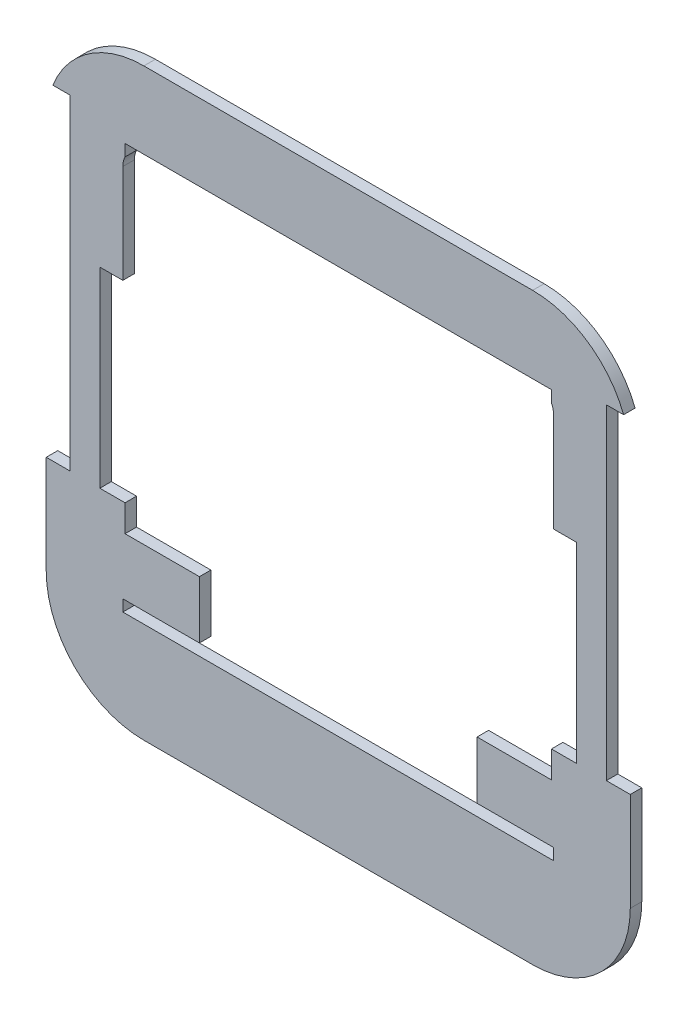
SolidWorks part; units mm, degrees
material "Teak"
ref_plane "Front Plane" through (0, 0, 0) normal (0, 0, 1) x (1, 0, 0)
ref_plane "Top Plane" through (0, 0, 0) normal (0, 1, 0) x (1, 0, 0)
ref_plane "Right Plane" through (0, 0, 0) normal (1, 0, 0) x (0, 0, -1)
sketch "Sketch1" plane through (0, 0, 0) normal (0, 0, 1) x (1, 0, 0)
  line L0 (76.25, -25) -> (70, -25)
  line L1 (70, -25) -> (70, 60)
  line L2 (70, 60) -> (74.5132, 60)
  line L6 (50.75, 76.25) -> (-50.75, 76.25)
  line L7 (-74.5132, 60) -> (-70, 60)
  line L8 (-70, 60) -> (-70, -25)
  line L9 (-70, -25) -> (-76.25, -25)
  line L10 (-76.25, -25) -> (-76.25, -50.75)
  line L11 (-50.75, -76.25) -> (50.75, -76.25)
  line L12 (76.25, -50.75) -> (76.25, -25)
  line L13 (56.25, -50) -> (56.25, -47)
  line L14 (49.7468, -50) -> (56.25, -50)
  line L15 (-49.7468, -50) -> (49.7468, -50)
  line L16 (-56.25, -50) -> (-49.7468, -50)
  line L17 (-56.25, -47) -> (-56.25, -50)
  line L18 (-49.7468, -47) -> (-56.25, -47)
  line L19 (-36.25, -47) -> (-49.7468, -47)
  line L20 (-36.25, -32) -> (-36.25, -47)
  line L21 (-55.6698, -32) -> (-36.25, -32)
  line L24 (-62.25, -25) -> (-56.25, -25)
  line L25 (-62.25, 25) -> (-62.25, -25)
  line L26 (-56.25, 25) -> (-62.25, 25)
  line L27 (-56.25, 50.75) -> (-56.25, 25)
  line L28 (-55.6698, 56.25) -> (-55.6698, 53.2088)
  line L29 (55.6698, 56.25) -> (-55.6698, 56.25)
  line L30 (55.6698, 53.2088) -> (55.6698, 56.25)
  line L31 (56.25, 25) -> (56.25, 50.75)
  line L32 (62.25, 25) -> (56.25, 25)
  line L33 (62.25, -25) -> (62.25, 25)
  line L34 (56.25, -25) -> (62.25, -25)
  line L37 (36.25, -32) -> (55.6698, -32)
  line L38 (36.25, -47) -> (36.25, -32)
  line L39 (49.7468, -47) -> (36.25, -47)
  line L40 (56.25, -47) -> (49.7468, -47)
  line L41 (55.6698, -32) -> (55.6698, -25)
  line L42 (55.6698, -25) -> (56.25, -25)
  line L43 (-55.6698, -32) -> (-55.6698, -25)
  line L44 (-55.6698, -25) -> (-56.25, -25)
  arc A0 (74.5132, 60) -> (60, 74.5132) centre (50.75, 50.75) ccw
  arc A1 (57, 75.4722) -> (50.75, 76.25) centre (50.75, 50.75) ccw
  arc A2 (-50.75, 76.25) -> (-74.5132, 60) centre (-50.75, 50.75) ccw
  arc A3 (-76.25, -50.75) -> (-50.75, -76.25) centre (-50.75, -50.75) ccw
  arc A4 (50.75, -76.25) -> (76.25, -50.75) centre (50.75, -50.75) ccw
  arc A6 (-55.6698, 53.2088) -> (-56.25, 50.75) centre (-50.75, 50.75) ccw
  arc A7 (56.25, 50.75) -> (55.6698, 53.2088) centre (50.75, 50.75) ccw
  arc A9 (60, 74.5132) -> (57, 75.4722) centre (50.75, 50.75) ccw
extrude "Boss-Extrude1" add sketch "Sketch1" along normal blind 3
